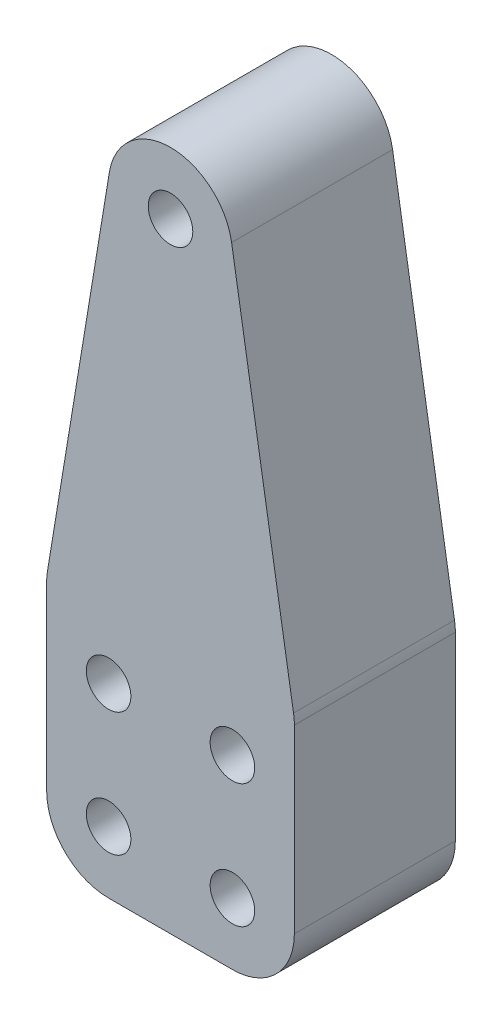
SolidWorks part; units mm, degrees
ref_plane "Front Plane" through (0, 0, 0) normal (0, 0, 1) x (1, 0, 0)
ref_plane "Top Plane" through (0, 0, 0) normal (0, 1, 0) x (1, 0, 0)
ref_plane "Right Plane" through (0, 0, 0) normal (1, 0, 0) x (0, 0, -1)
sketch "Sketch1" plane through (0, 0, 0) normal (0, 0, 1) x (1, 0, 0)
  line L0 (-12.7, 12.7) -> (-6.2659, 51.8303)
  line L1 (12.7, -12.7) -> (-12.7, -12.7)
  line L2 (12.7, -12.7) -> (12.7, 12.7)
  line L4 (-12.7, -12.7) -> (-12.7, 12.7)
  line L5 (12.7, -12.7) -> (-12.7, 12.7) construction
  line L6 (12.7, 12.7) -> (-12.7, -12.7) construction
  line L8 (6.2659, 51.8303) -> (12.7, 12.7)
  circle A0 centre (-6.35, -6.35) radius 2.286
  circle A1 centre (0, 50.8) radius 2.286
  arc A2 (6.2659, 51.8303) -> (-6.2659, 51.8303) centre (0, 50.8) ccw
  circle A3 centre (6.35, -6.35) radius 2.286
  circle A4 centre (6.35, 6.35) radius 2.286
  circle A5 centre (-6.35, 6.35) radius 2.286
  point P0 (0, 0)
  dimension "D3" = 6.35
  dimension "D4" = 4.572
  dimension "D5" = 12.7
  dimension "D1" = 25.4
  dimension "D2" = 25.4
  dimension "D6" = 50.8
  dimension "D7" = 2
  dimension "D8" = 2
extrude "Boss-Extrude1" add sketch "Sketch1" along normal blind 16.51
fillet "Fillet1" radius 6.35 4 edges at (-12.7, 12.7, 8.255) (12.7, 12.7, 8.255) (12.7, -12.7, 8.255) (-12.7, -12.7, 8.255)
